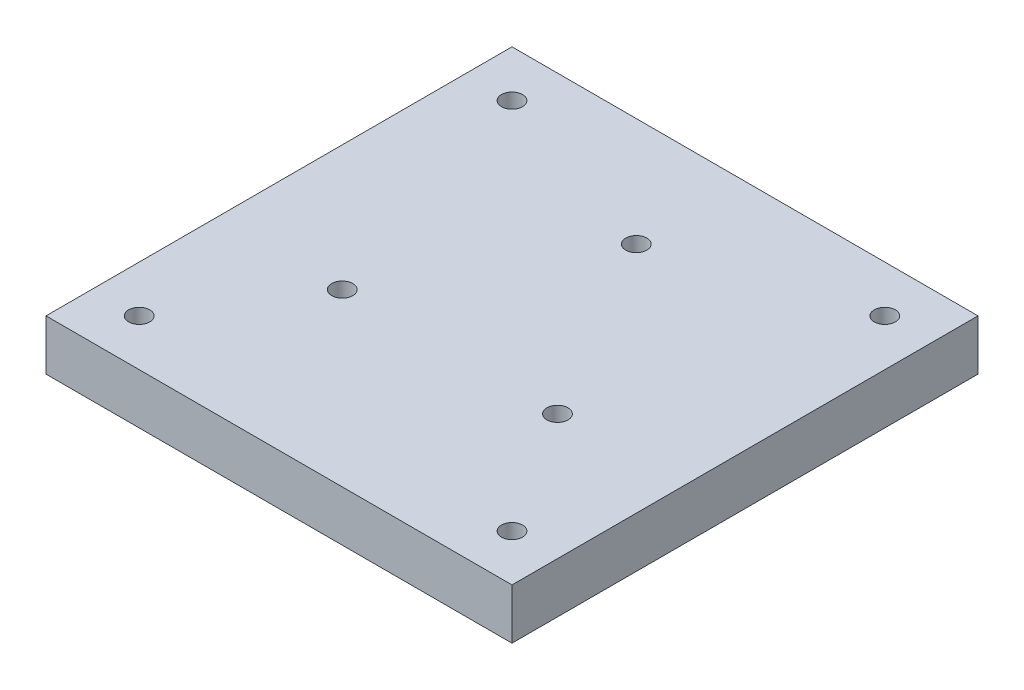
SolidWorks part; units mm, degrees
ref_plane "Front Plane" through (0, 0, 0) normal (0, 0, 1) x (1, 0, 0)
ref_plane "Top Plane" through (0, 0, 0) normal (0, 1, 0) x (1, 0, 0)
ref_plane "Right Plane" through (0, 0, 0) normal (1, 0, 0) x (0, 0, -1)
sketch "Sketch1" plane through (0, 0, 0) normal (0, 0, 1) x (1, 0, 0)
  line L7 (-50.8, -5.5562) -> (50.8, -5.5562)
  line L8 (-50.8, -5.5562) -> (-50.8, 5.5562)
  line L9 (-50.8, 5.5562) -> (50.8, 5.5562)
  line L10 (50.8, -5.5562) -> (50.8, 5.5562)
  line L11 (-50.8, -5.5562) -> (50.8, 5.5562) construction
  line L12 (-50.8, 5.5562) -> (50.8, -5.5562) construction
  point P4 (0, 0)
  point P14 (0, 0)
  dimension "Width" = 101.6
  dimension "Thickness" = 11.1125
sketch "Sketch2" plane through (0, 0, 0) normal (0, 1, 0) x (0, 0, -1)
  line L0 (50.8, 50.8) -> (-50.8, 50.8) construction
  point P0 (76.2, 50.8)
  point P4 (0, 50.8)
  point P6 (-76.2, 50.8)
  dimension "Length" = 101.6
  dimension "D1" = 127
  dimension "D2" = 127
sketch "Sketch3" plane through (0, 0, 0) normal (0, 0, 1) x (1, 0, 0)
  line L6 (-50.8, 5.5562) -> (50.8, 5.5562)
  line L7 (50.8, 5.5562) -> (50.8, -5.5562)
  line L8 (50.8, -5.5562) -> (-50.8, -5.5562)
  line L9 (-50.8, -5.5562) -> (-50.8, 5.5562)
extrude "Boss-Extrude1" add sketch "Sketch3" along normal mid plane 101.6
ref_plane "FacingTop" through (0, 5.1594, 0) normal (0, 1, 0) x (1, 0, 0)
other "FacingTopSurfaceCut"
ref_plane "FacingBottom" through (0, -5.1594, 0) normal (0, -1, 0) x (-1, 0, 0)
other "FacingBottomSurfaceCut"
sketch "BaseBorderRadiusSketch" plane through (0, 5.1594, 0) normal (0, 1, 0) x (1, 0, 0)
  line L0 (50.8, -50.8) -> (50.8, 50.8) construction
  line L1 (-47.625, -47.625) -> (47.625, -47.625)
  line L2 (-47.625, -47.625) -> (-47.625, 47.625)
  line L3 (-47.625, 47.625) -> (47.625, 47.625)
  line L4 (47.625, -47.625) -> (47.625, 47.625)
  line L5 (-47.625, -47.625) -> (47.625, 47.625) construction
  line L6 (-47.625, 47.625) -> (47.625, -47.625) construction
  point P0 (0, 0)
  dimension "D1" = 3.175
extrude "BaseBorderRadiusCut-Extrude" cut sketch "BaseBorderRadiusSketch" against normal through all flip side to cut
sketch "BumperInsetSketch" plane through (0, -5.1594, 0) normal (0, -1, 0) x (1, 0, 0)
  line L0 (0, 0) -> (0, -25.4) construction
  line L1 (-38.1, -38.1) -> (38.1, -38.1) construction
  line L2 (-38.1, -38.1) -> (-38.1, 38.1) construction
  line L3 (-38.1, 38.1) -> (38.1, 38.1) construction
  line L4 (38.1, -38.1) -> (38.1, 38.1) construction
  line L5 (-38.1, -38.1) -> (38.1, 38.1) construction
  line L6 (-38.1, 38.1) -> (38.1, -38.1) construction
  line L7 (47.625, 47.625) -> (47.625, -47.625) construction
  line L8 (0, 0) -> (-21.997, 12.7) construction
  line L9 (0, 0) -> (21.997, 12.7) construction
  circle A0 centre (-38.1, 38.1) radius 5.715
  circle A1 centre (38.1, 38.1) radius 5.715
  circle A2 centre (38.1, -38.1) radius 5.715
  circle A3 centre (-38.1, -38.1) radius 5.715
  circle A4 centre (-21.997, 12.7) radius 5.715
  circle A5 centre (21.997, 12.7) radius 5.715
  circle A6 centre (0, -25.4) radius 5.715
  point P0 (0, 0)
  point P19 (0, 0)
  dimension "D2" = 11.43
  dimension "D1" = 9.525
  dimension "D3" = 25.4
  dimension "D4" = 3
hole_wizard "Bumper#6-32 Tapped Hole" positions "3DSketch4" profile "Sketch11" counterbore size "#6" standard "ANSI Inch" end condition through all
sketch3d "3DSketch4"
  point P0 (-38.1, -5.1594, 38.1)
  point P3 (-21.997, -5.1594, 12.7)
  point P6 (21.997, -5.1594, 12.7)
  point P9 (0, -5.1594, -25.4)
sketch "Sketch11" plane through (-38.1, -5.1594, 38.1) normal (1, 0, 0) x (0, 0, -1)
  line L0 (0, 0) -> (0, 10.3187)
  line L1 (0, 10.3187) -> (2.1526, 10.3187)
  line L3 (2.1526, 10.3187) -> (2.1526, 5.3848)
  line L4 (2.1526, 5.3848) -> (3.9688, 5.3848)
  line L5 (3.9688, 5.3848) -> (3.9688, 0)
  line L7 (3.9688, 0) -> (0, 0)
  line L11 (0, -6.35) -> (0, 107.95) construction
  dimension "Thru Hole Dia." = 4.3053
  dimension "Thru Hole Depth" = 10.3187
  dimension "C'Bore Dia." = 7.9375
  dimension "C'Bore Depth" = 5.3848
pattern_linear "BumperThreadLPattern" count 2 spacing 76.2 along (0, 0, -1) count 2 spacing 76.2 along (1, 0, 0) of "Bumper#6-32 Tapped Hole"
equation "\"D1@Boss-Extrude1\" = \"Length@Sketch2\""
equation "\"D1@Sketch2\"=\"Width@Sketch1\" * 1.25"
equation "\"D2@Sketch2\"=\"D1@Sketch2\""
